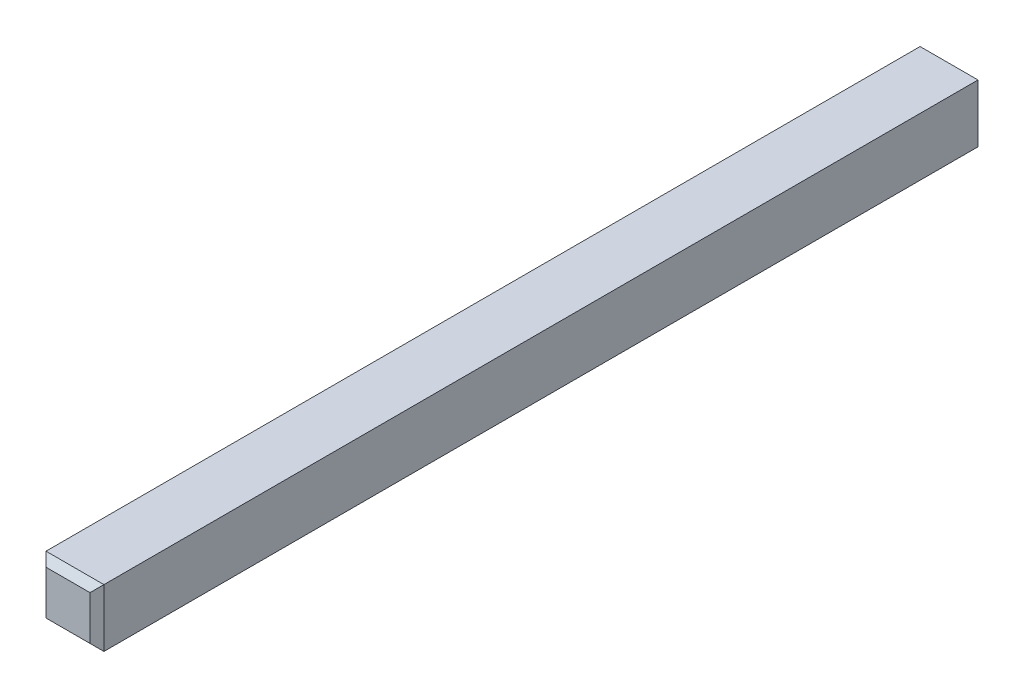
SolidWorks part; units mm, degrees
material "Alloy Steel"
ref_plane "Front Plane" through (0, 0, 0) normal (0, 0, 1) x (1, 0, 0)
ref_plane "Top Plane" through (0, 0, 0) normal (0, 1, 0) x (1, 0, 0)
ref_plane "Right Plane" through (0, 0, 0) normal (1, 0, 0) x (0, 0, -1)
sketch "Sketch1" plane through (0, 0, 0) normal (0, 0, 1) x (1, 0, 0)
  line L1 (0, 0) -> (0.75, 0)
  line L2 (0, 0) -> (0, 0.75)
  line L3 (0, 0.75) -> (0.75, 0.75)
  line L4 (0.75, 0) -> (0.75, 0.75)
  dimension "D1" = 0.75
  dimension "D2" = 0.75
extrude "Boss-Extrude1" add sketch "Sketch1" along normal blind 11.5
chamfer "Chamfer1" distance 0.09 angle 45 8 edges at (0.375, 0, 0) (0.75, 0.375, 0) (0.375, 0.75, 0) (0, 0.375, 0) (0.375, 0, 11.5) (0.75, 0.375, 11.5) (0, 0.375, 11.5) (0.375, 0.75, 11.5)
